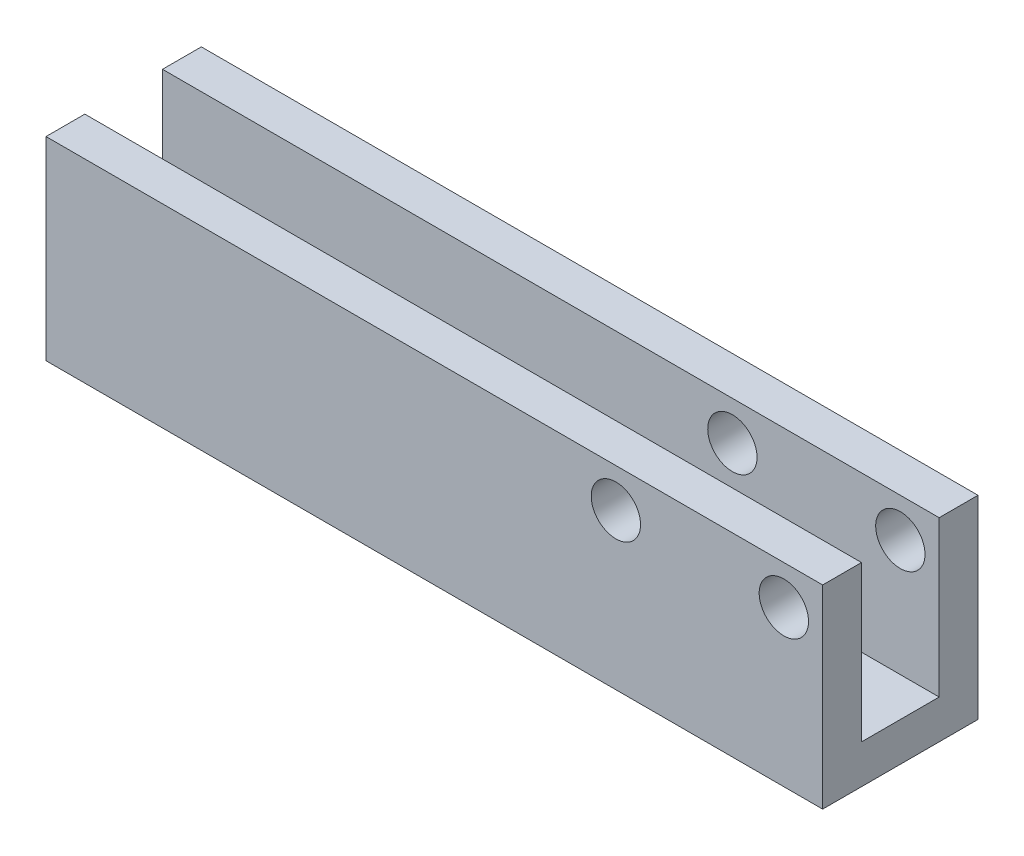
SolidWorks part; units mm, degrees
ref_plane "Front Plane" through (0, 0, 0) normal (0, 0, 1) x (1, 0, 0)
ref_plane "Top Plane" through (0, 0, 0) normal (0, 1, 0) x (1, 0, 0)
ref_plane "Right Plane" through (0, 0, 0) normal (1, 0, 0) x (0, 0, -1)
sketch "Sketch1" plane through (0, 0, 0) normal (0, 0, 1) x (1, 0, 0)
  line L1 (-100, -25) -> (100, -25)
  line L2 (-100, -25) -> (-100, 25)
  line L3 (-100, 25) -> (100, 25)
  line L4 (100, -25) -> (100, 25)
  line L5 (-100, -25) -> (100, 25) construction
  line L6 (-100, 25) -> (100, -25) construction
  point P0 (0, 0)
  dimension "D1" = 200
  dimension "D2" = 50
extrude "Boss-Extrude1" add sketch "Sketch1" along normal blind 40
sketch "Sketch2" plane through (0, 0, 40) normal (0, 0, 1) x (1, 0, 0)
  line L0 (100, -25) -> (100, 25) construction
  line L2 (100, 25) -> (-100, 25) construction
  circle A0 centre (90, 15) radius 6.35
  circle A1 centre (46.75, 15) radius 6.35
  dimension "D1" = 12.7
  dimension "D2" = 12.7
  dimension "D3" = 10
  dimension "D4" = 10
  dimension "D5" = 10
  dimension "D6" = 43.25
extrude "Cut-Extrude1" cut sketch "Sketch2" against normal through all
sketch "Sketch4" plane through (-100, 0, 0) normal (-1, 0, 0) x (0, 0, 1)
  line L0 (40, 25) -> (0, 25) construction
  line L1 (10, 25) -> (30, 25)
  line L2 (10, 25) -> (10, -15)
  line L3 (10, -15) -> (30, -15)
  line L4 (30, 25) -> (30, -15)
  line L5 (0, 25) -> (0, -25) construction
  line L6 (40, 25) -> (40, -25) construction
  line L7 (40, -25) -> (0, -25) construction
  dimension "D1" = 10
  dimension "D2" = 10
  dimension "D3" = 10
extrude "Cut-Extrude2" cut sketch "Sketch4" against normal through all
